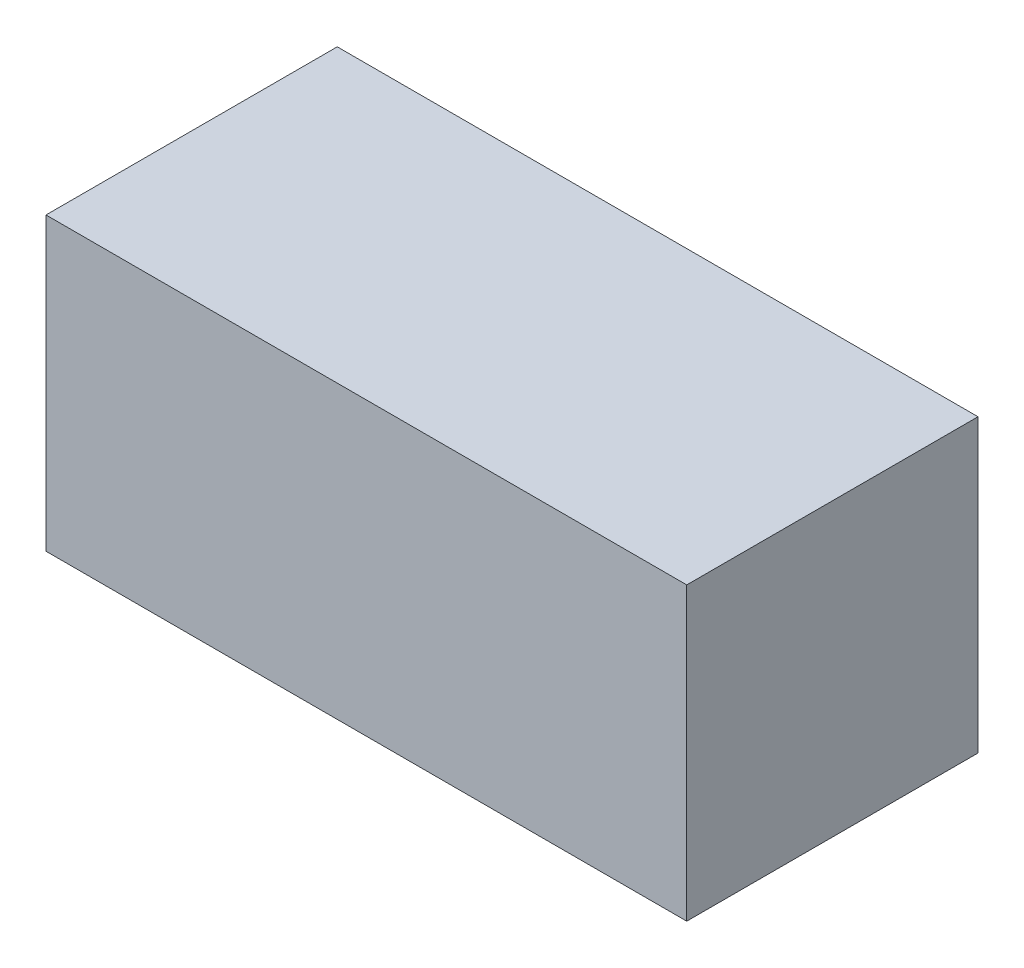
SolidWorks part; units mm, degrees
material "AISI 1035 Сталь (SS)"
ref_plane "Спереди" through (0, 0, 0) normal (0, 0, 1) x (1, 0, 0)
ref_plane "Сверху" through (0, 0, 0) normal (0, 1, 0) x (1, 0, 0)
ref_plane "Справа" through (0, 0, 0) normal (1, 0, 0) x (0, 0, -1)
sketch "Эскиз1" plane through (0, 0, 0) normal (0, 0, 1) x (1, 0, 0)
  line L1 (44.0503, 37.6311) -> (110.0503, 37.6311)
  line L2 (44.0503, 37.6311) -> (44.0503, 7.6311)
  line L3 (44.0503, 7.6311) -> (110.0503, 7.6311)
  line L4 (110.0503, 37.6311) -> (110.0503, 7.6311)
  dimension "D1" = 66
  dimension "D2" = 30
extrude "Бобышка-Вытянуть1" add sketch "Эскиз1" along normal blind 30
